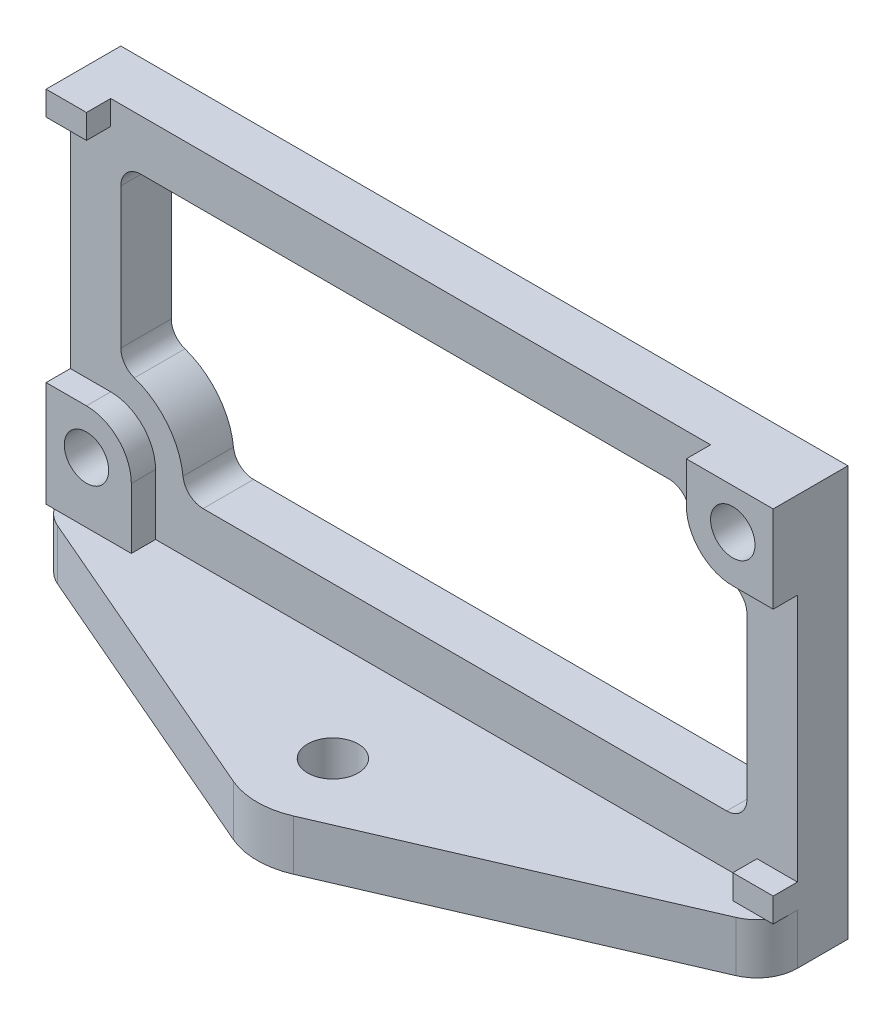
SolidWorks part; units mm, degrees
ref_plane "Front Plane" through (0, 0, 0) normal (0, 0, 1) x (1, 0, 0)
ref_plane "Top Plane" through (0, 0, 0) normal (0, 1, 0) x (1, 0, 0)
ref_plane "Right Plane" through (0, 0, 0) normal (1, 0, 0) x (0, 0, -1)
sketch "Sketch1" plane through (0, 0, 0) normal (0, 0, 1) x (1, 0, 0)
  line L1 (0, 0) -> (45.72, 0)
  line L2 (0, 0) -> (0, 22.606)
  line L3 (0, 22.606) -> (45.72, 22.606)
  line L4 (45.72, 0) -> (45.72, 22.606)
  circle A0 centre (2.54, 3.81) radius 1.397
  circle A1 centre (43.18, 20.066) radius 1.397
  dimension "D1" = 2.794
  dimension "D2" = 2.794
  dimension "D3" = 45.72
  dimension "D4" = 22.606
  dimension "D5" = 3.81
  dimension "D6" = 2.54
  dimension "D7" = 2.54
  dimension "D8" = 2.54
extrude "Boss-Extrude1" add sketch "Sketch1" along normal blind 3.175
sketch "Sketch3" plane through (0, 0, 0) normal (0, 1, 0) x (1, 0, 0)
  line L1 (0, -3.175) -> (0, 0)
  line L2 (22.86, -14.7122) -> (22.86, 0) construction
  line L3 (1.5334, -5.507) -> (20.9727, -13.8976)
  line L4 (24.7473, -13.8976) -> (44.1866, -5.507)
  line L5 (45.72, -3.175) -> (45.72, 0)
  line L6 (45.72, 0) -> (0, 0)
  line L8 (45.72, -3.175) -> (0, -3.175) construction
  arc A0 (44.1866, -5.507) -> (45.72, -3.175) centre (43.18, -3.175) ccw
  arc A1 (0, -3.175) -> (1.5334, -5.507) centre (2.54, -3.175) ccw
  circle A2 centre (22.86, -9.525) radius 1.5875
  arc A3 (20.9727, -13.8976) -> (24.7473, -13.8976) centre (22.86, -9.525) ccw
  point P11 (45.72, -4.8452)
  point P14 (0, -4.8452)
  dimension "D1" = 3.175
  dimension "D2" = 2.54
  dimension "D3" = 3.175
  dimension "D4" = 6.35
extrude "Boss-Extrude2" add sketch "Sketch3" against normal blind 3.175
sketch "Sketch4" plane through (0, 0, 0) normal (0, 0, 1) x (1, 0, 0)
  line L0 (3.175, 18.161) -> (3.175, 9.3327)
  line L3 (8.3474, 3.175) -> (41.275, 3.175)
  line L4 (42.545, 4.445) -> (42.545, 14.5433)
  line L7 (37.6573, 19.431) -> (4.445, 19.431)
  line L8 (0, 22.606) -> (0, 0) construction
  line L9 (45.72, 0) -> (45.72, 22.606) construction
  line L10 (0, 0) -> (45.72, 0) construction
  line L11 (45.72, 22.606) -> (0, 22.606) construction
  arc A1 (7.0849, 4.307) -> (4.0309, 8.1321) centre (2.54, 3.81) ccw
  arc A2 (38.8579, 18.5751) -> (41.6891, 15.7439) centre (43.18, 20.066) ccw
  circle A3 centre (2.54, 3.81) radius 1.397 construction
  circle A4 centre (43.18, 20.066) radius 1.397 construction
  arc A5 (41.275, 3.175) -> (42.545, 4.445) centre (41.275, 4.445) ccw
  arc A6 (42.545, 14.5433) -> (41.6891, 15.7439) centre (41.275, 14.5433) ccw
  arc A7 (37.6573, 19.431) -> (38.8579, 18.5751) centre (37.6573, 18.161) cw
  arc A8 (3.175, 9.3327) -> (4.0309, 8.1321) centre (4.445, 9.3327) ccw
  arc A9 (3.175, 18.161) -> (4.445, 19.431) centre (4.445, 18.161) cw
  arc A10 (8.3474, 3.175) -> (7.0849, 4.307) centre (8.3474, 4.445) cw
  dimension "D5" = 3.175
  dimension "D6" = 3.175
  dimension "D7" = 1.27
  dimension "D8" = 1.27
  dimension "D1" = 3.175
  dimension "D2" = 3.175
  dimension "D3" = 3.175
  dimension "D4" = 3.175
extrude "Cut-Extrude1" cut sketch "Sketch4" along normal through all
sketch "Sketch5" plane through (0, 0, 3.175) normal (0, 0, 1) x (1, 0, 0)
  line L0 (2.54, 6.6294) -> (0, 6.6294)
  line L1 (0, 22.606) -> (0, 0) construction
  line L2 (0, 6.6294) -> (0, 0)
  line L3 (0, 0) -> (5.3594, 0)
  line L4 (0, 0) -> (45.72, 0) construction
  line L5 (5.3594, 0) -> (5.3594, 3.81)
  line L6 (40.259, 20.066) -> (40.259, 22.606)
  line L7 (45.72, 22.606) -> (0, 22.606) construction
  line L8 (40.259, 22.606) -> (45.72, 22.606)
  line L9 (45.72, 22.606) -> (45.72, 17.145)
  line L10 (45.72, 0) -> (45.72, 22.606) construction
  line L11 (45.72, 17.145) -> (43.18, 17.145)
  line L13 (0, 22.606) -> (2.54, 22.606)
  line L14 (0, 22.606) -> (0, 21.082)
  line L15 (0, 21.082) -> (2.54, 21.082)
  line L16 (2.54, 22.606) -> (2.54, 21.082)
  line L17 (45.72, 0) -> (43.18, 0)
  line L18 (45.72, 0) -> (45.72, 1.524)
  line L19 (45.72, 1.524) -> (43.18, 1.524)
  line L20 (43.18, 0) -> (43.18, 1.524)
  arc A0 (5.3594, 3.81) -> (2.54, 6.6294) centre (2.54, 3.81) ccw
  circle A1 centre (2.54, 3.81) radius 1.397 construction
  arc A2 (40.259, 20.066) -> (43.18, 17.145) centre (43.18, 20.066) ccw
  circle A3 centre (43.18, 20.066) radius 1.397 construction
  circle A4 centre (2.54, 3.81) radius 1.397
  circle A5 centre (43.18, 20.066) radius 1.397
  dimension "D1" = 1.4224
  dimension "D2" = 1.524
  dimension "D3" = 1.524
  dimension "D4" = 2.54
  dimension "D5" = 2.54
  dimension "D6" = 1.524
extrude "Boss-Extrude3" add sketch "Sketch5" along normal blind 1.524
